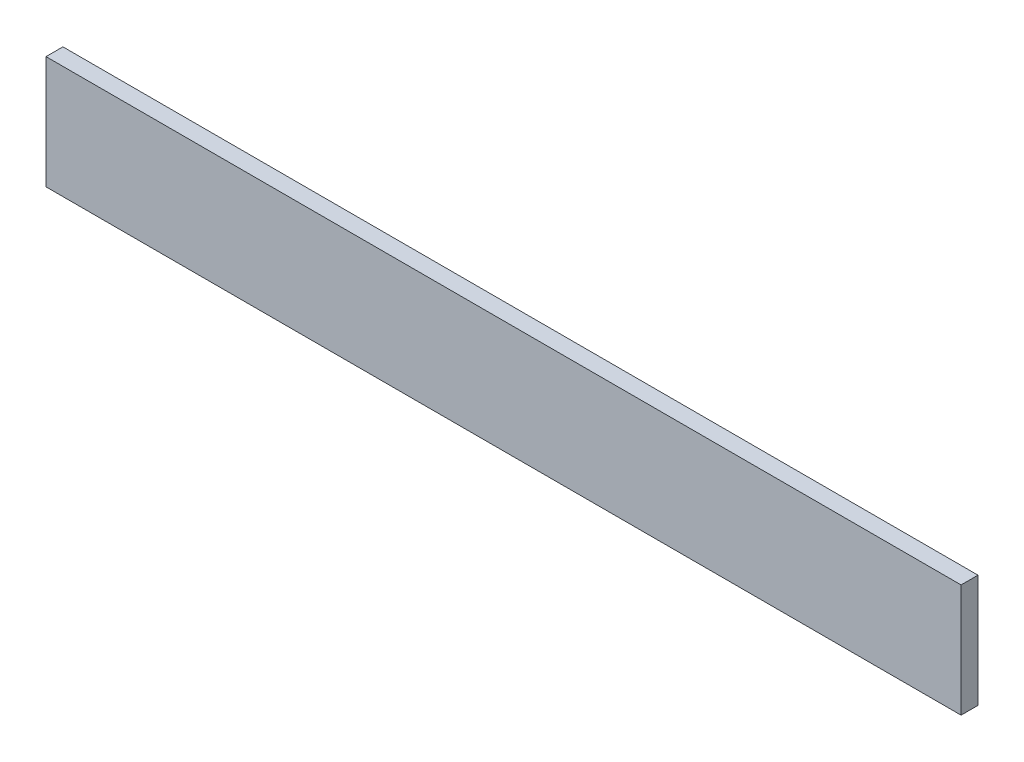
SolidWorks part; units mm, degrees
ref_plane "Alzado" through (0, 0, 0) normal (0, 0, 1) x (1, 0, 0)
ref_plane "Planta" through (0, 0, 0) normal (0, 1, 0) x (1, 0, 0)
ref_plane "Vista lateral" through (0, 0, 0) normal (1, 0, 0) x (0, 0, -1)
sketch "Croquis1" plane through (0, 0, 0) normal (0, 0, 1) x (1, 0, 0)
  line L1 (-405.6, -50) -> (405.6, -50)
  line L2 (-405.6, -50) -> (-405.6, 50)
  line L3 (-405.6, 50) -> (405.6, 50)
  line L4 (405.6, -50) -> (405.6, 50)
  line L5 (-405.6, -50) -> (405.6, 50) construction
  line L6 (-405.6, 50) -> (405.6, -50) construction
  point P0 (0, 0)
  dimension "D1" = 811.2
  dimension "D2" = 100
extrude "Saliente-Extruir1" add sketch "Croquis1" along normal blind 15
sketch "Croquis2" plane through (0, 0, 15) normal (0, 0, 1) x (1, 0, 0)
  line L0 (0, -50) -> (0, 50) construction
  line L1 (-405.6, -50) -> (405.6, -50) construction
  line L2 (405.6, 50) -> (-405.6, 50) construction
sketch "Croquis3" plane through (0, 50, 0) normal (0, 1, 0) x (1, 0, 0)
  line L0 (0, -15) -> (0, 0) construction
  line L1 (405.6, -15) -> (-405.6, -15) construction
  line L2 (405.6, 0) -> (-405.6, 0) construction
